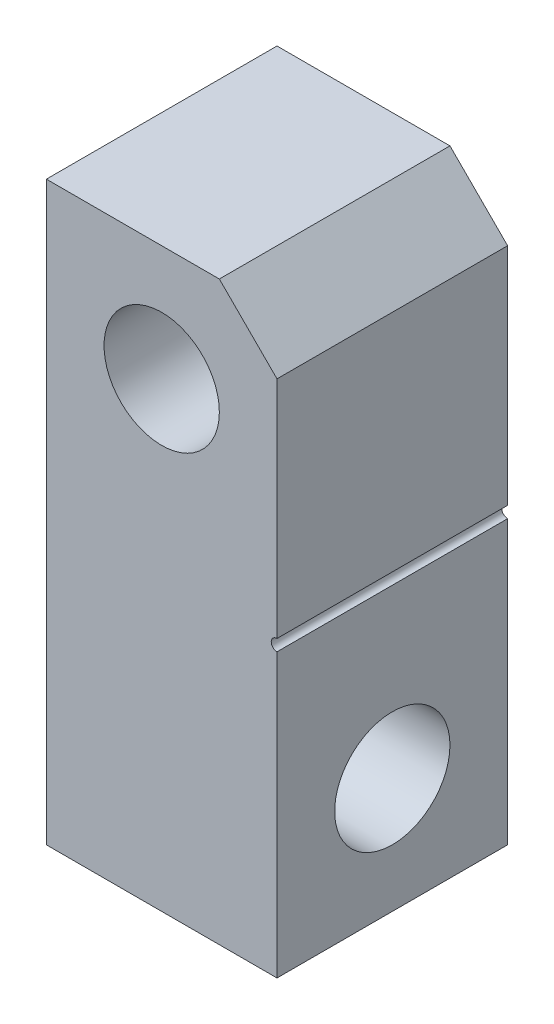
SolidWorks part; units mm, degrees
material "1060 Alloy"
ref_plane "Front Plane" through (0, 0, 0) normal (0, 0, 1) x (1, 0, 0)
ref_plane "Top Plane" through (0, 0, 0) normal (0, 1, 0) x (1, 0, 0)
ref_plane "Right Plane" through (0, 0, 0) normal (1, 0, 0) x (0, 0, -1)
sketch "Sketch1" plane through (0, 0, 0) normal (0, 0, 1) x (1, 0, 0)
  line L0 (0, 0) -> (20, 0)
  line L1 (20, 0) -> (20, 50)
  line L2 (20, 50) -> (0, 50)
  line L3 (0, 50) -> (0, 0)
  dimension "D1" = 20
  dimension "D2" = 50
extrude "Boss-Extrude1" add sketch "Sketch1" against normal blind 20
sketch "Sketch2" plane through (0, 0, 0) normal (0, 0, 1) x (1, 0, 0)
  line L0 (20, 50) -> (20, 45)
  line L1 (20, 0) -> (20, 50) construction
  line L2 (20, 50) -> (15, 50)
  line L3 (20, 50) -> (0, 50) construction
  line L4 (15, 50) -> (20, 45)
  dimension "D1" = 5
  dimension "D2" = 5
extrude "Cut-Extrude1" cut sketch "Sketch2" against normal through all
sketch "Sketch3" plane through (20, 0, 0) normal (1, 0, 0) x (0, 0, -1)
  line L0 (20, 0) -> (0, 0) construction
  line L1 (20, 0) -> (20, 45) construction
  circle A0 centre (10, 10) radius 5
  dimension "D2" = 10
  dimension "D3" = 10
  dimension "D1" = 10
extrude "Cut-Extrude2" cut sketch "Sketch3" against normal through all
sketch "Sketch4" plane through (0, 0, 0) normal (0, 0, 1) x (1, 0, 0)
  line L0 (0, 50) -> (0, 0) construction
  line L1 (15, 50) -> (0, 50) construction
  circle A0 centre (10, 40) radius 5
  point P6 (7.8771, 44.4745)
  dimension "D2" = 10
  dimension "D3" = 10
  dimension "D1" = 10
extrude "Cut-Extrude3" cut sketch "Sketch4" against normal through all
sketch "Sketch5" plane through (0, 0, 0) normal (0, 0, 1) x (1, 0, 0)
  line L0 (20, 0) -> (20, 45) construction
  line L1 (0, 0) -> (20, 0) construction
  circle A0 centre (20, 25) radius 0.5
  dimension "D2" = 1
  dimension "D1" = 25
extrude "Cut-Extrude4" cut sketch "Sketch5" against normal through all
